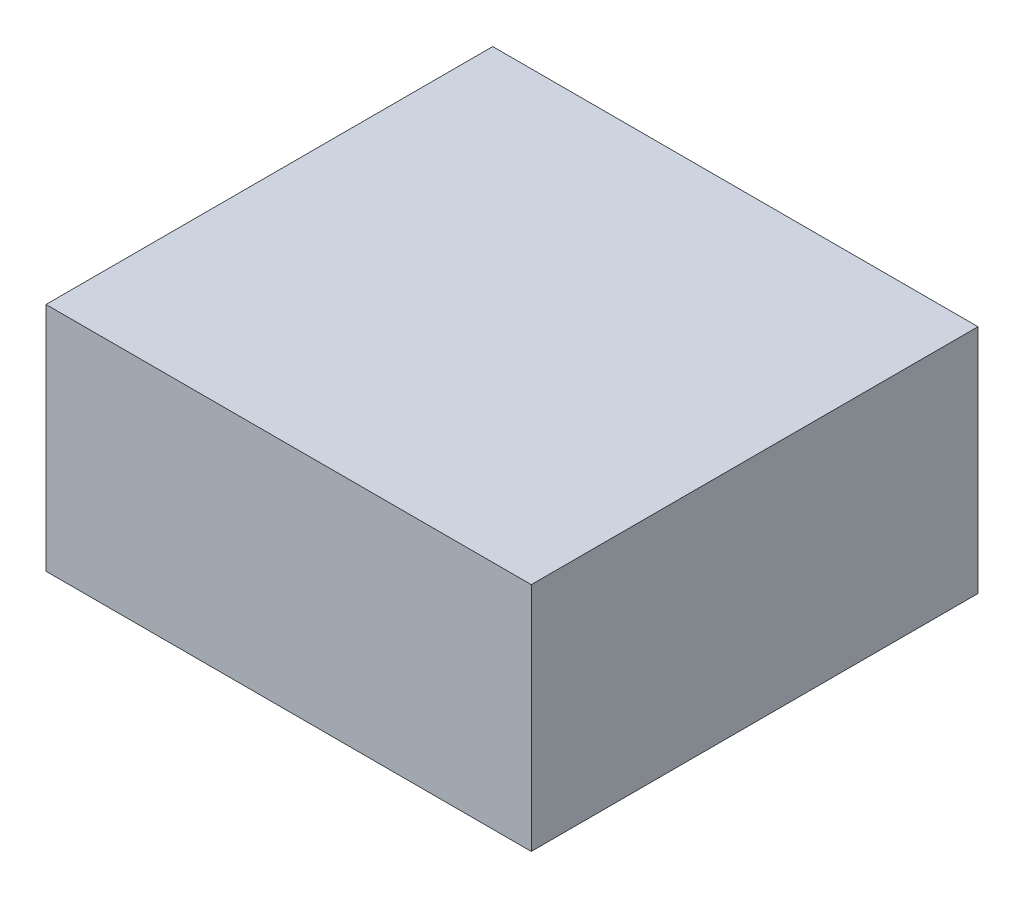
SolidWorks part; units mm, degrees
ref_plane "Спереди" through (0, 0, 0) normal (0, 0, 1) x (1, 0, 0)
ref_plane "Сверху" through (0, 0, 0) normal (0, 1, 0) x (1, 0, 0)
ref_plane "Справа" through (0, 0, 0) normal (1, 0, 0) x (0, 0, -1)
other "Configuration Table"
sketch "Эскиз1" plane through (0, 0, 0) normal (0, 1, 0) x (1, 0, 0)
  line L1 (0, 0) -> (63, 0)
  line L2 (0, 0) -> (0, -58)
  line L3 (0, -58) -> (63, -58)
  line L4 (63, 0) -> (63, -58)
  dimension "D1" = 63
  dimension "D2" = 58
extrude "Бобышка-Вытянуть1" add sketch "Эскиз1" along normal blind 30
